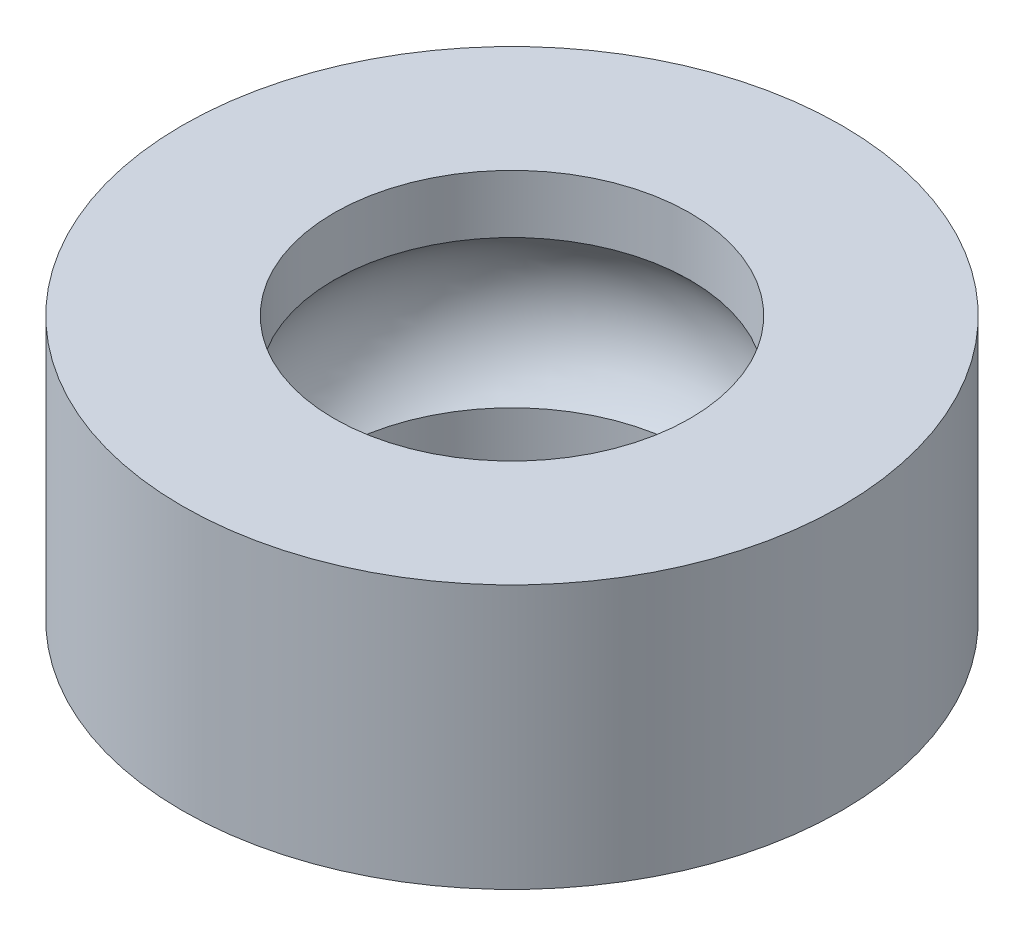
SolidWorks part; units mm, degrees
ref_plane "Front Plane" through (0, 0, 0) normal (0, 0, 1) x (1, 0, 0)
ref_plane "Top Plane" through (0, 0, 0) normal (0, 1, 0) x (1, 0, 0)
ref_plane "Right Plane" through (0, 0, 0) normal (1, 0, 0) x (0, 0, -1)
sketch "Sketch1" plane through (0, 0, 0) normal (0, 0, 1) x (1, 0, 0)
  line L0 (0, 0) -> (0, 12.6695) construction
  line L1 (2.7, 4) -> (2.7, 3.118)
  line L2 (2.7, 0) -> (5, 0)
  line L3 (5, 0) -> (5, 4)
  line L4 (5, 4) -> (2.7, 4)
  line L5 (2.7, 4) -> (2.7, 3.118) construction
  line L6 (2.7, 2) -> (1.7, 2) construction
  line L7 (2.7, 0.882) -> (2.7, 0)
  line L8 (2.7, 0.882) -> (2.7, 0) construction
  arc A0 (2.7, 0.882) -> (2.7, 3.118) centre (1.7, 2) ccw
  dimension "D5" = 3
  dimension "D1" = 4
  dimension "D2" = 2.3
  dimension "D3" = 2.7
  dimension "D4" = 1
revolve "Revolve1" add sketch "Sketch1" angle 360 about L0
